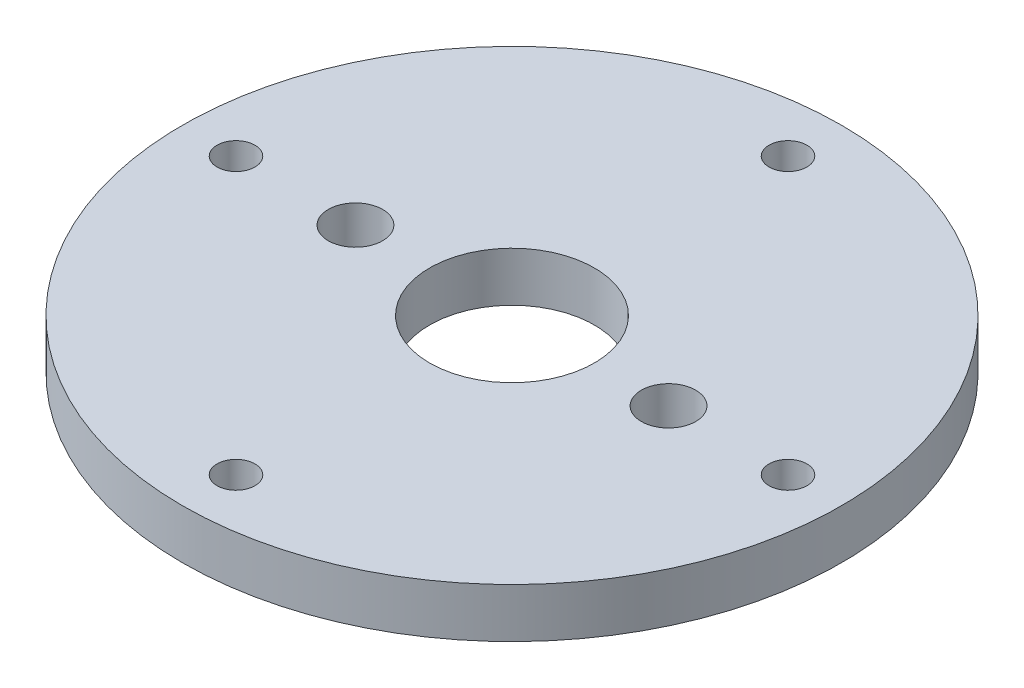
SolidWorks part; units mm, degrees
ref_plane "前视基准面" through (0, 0, 0) normal (0, 0, 1) x (1, 0, 0)
ref_plane "上视基准面" through (0, 0, 0) normal (0, 1, 0) x (1, 0, 0)
ref_plane "右视基准面" through (0, 0, 0) normal (1, 0, 0) x (0, 0, -1)
sketch "草图1" plane through (0, 0, 0) normal (0, 1, 0) x (1, 0, 0)
  circle A0 centre (0, 0) radius 20
  dimension "D1" = 40
extrude "凸台-拉伸1" add sketch "草图1" along normal blind 3
sketch "草图2" plane through (0, 3, 0) normal (0, 1, 0) x (1, 0, 0)
  circle A0 centre (0, 0) radius 16.75 construction
  circle A1 centre (0, 16.75) radius 1.15
  circle A2 centre (16.75, 0) radius 1.15
  circle A3 centre (0, -16.75) radius 1.15
  circle A4 centre (-16.75, 0) radius 1.15
  dimension "D1" = 33.5
  dimension "D2" = 2.3
extrude "切除-拉伸1" cut sketch "草图2" against normal up to next
sketch "草图3" plane through (0, 3, 0) normal (0, 1, 0) x (1, 0, 0)
  line L0 (-9.5, 0) -> (9.5, 0) construction
  circle A0 centre (-9.5, 0) radius 1.65
  circle A1 centre (9.5, 0) radius 1.65
  circle A2 centre (0, 0) radius 5
  point P4 (0, 0)
  dimension "D2" = 3.3
  dimension "D3" = 10
  dimension "D1" = 19
extrude "切除-拉伸2" cut sketch "草图3" against normal up to next
